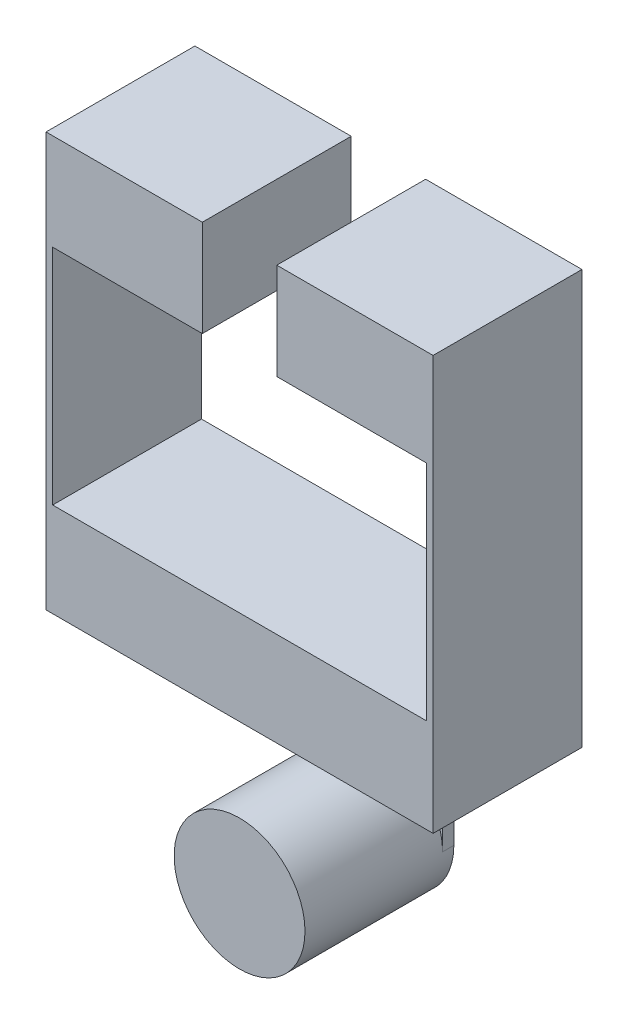
SolidWorks part; units mm, degrees
other "Markup1"
sketch "Sketch7" plane through (31.7043, 97.4003, 0) normal (0.5774, 0.5773, 0.5774) x (0.7071, 0, -0.7071)
material "ASTM A36 Steel"
ref_plane "Front Plane" through (0, 0, 0) normal (0, 0, 1) x (1, 0, 0)
ref_plane "Top Plane" through (0, 0, 0) normal (0, 1, 0) x (1, 0, 0)
ref_plane "Right Plane" through (0, 0, 0) normal (1, 0, 0) x (0, 0, -1)
sketch "Sketch1" plane through (0, 0, 0) normal (0, 0, 1) x (1, 0, 0)
  circle A0 centre (0, 0) radius 11.1628
  dimension "D1" = 22.3256
extrude "Boss-Extrude1" add sketch "Sketch1" against normal blind 25.4
sketch "Sketch2" plane through (0, 0, -25.4) normal (0, 0, -1) x (-1, 0, 0)
  line L0 (-11.1628, 0) -> (-11.1628, 25.4)
  line L1 (-11.1628, 25.4) -> (11.1628, 25.4)
  line L2 (11.1628, 25.4) -> (11.1628, 0)
  circle A0 centre (0, 0) radius 11.1628 construction
  arc A1 (11.1628, 0) -> (-11.1628, 0) centre (0, 0) ccw
  dimension "D1" = 22.3256
  dimension "D2" = 25.4
extrude "Boss-Extrude2" add sketch "Sketch2" against normal blind 1.9264
ref_plane "Plane1" through (0, 25.4, 0) normal (0, 1, 0) x (1, 0, 0)
sketch "Sketch4" plane through (0, 25.4, 0) normal (0, 1, 0) x (1, 0, 0)
  line L0 (0, 0) -> (0, 55.2267) construction
  line L1 (-33.02, 0) -> (33.02, 0)
  line L2 (-33.02, 0) -> (-33.02, 25.4)
  line L3 (-33.02, 25.4) -> (33.02, 25.4)
  line L4 (33.02, 0) -> (33.02, 25.4)
  point P6 (0, 0)
  dimension "D1" = 25.4
  dimension "D2" = 66.04
extrude "Boss-Extrude3" add sketch "Sketch4" along normal blind 16.0644
sketch "Sketch5" plane through (0, 41.4644, 0) normal (0, 1, 0) x (1, 0, 0)
  line L0 (-33.02, 0) -> (33.02, 0) construction
  line L1 (-33.02, 25.4) -> (-31.8904, 25.4)
  line L2 (-33.02, 25.4) -> (-33.02, 0)
  line L3 (-33.02, 0) -> (-31.8904, 0)
  line L4 (-31.8904, 25.4) -> (-31.8904, 0)
  line L6 (33.02, 25.4) -> (31.8904, 25.4)
  line L7 (33.02, 25.4) -> (33.02, 0)
  line L8 (33.02, 0) -> (31.8904, 0)
  line L9 (31.8904, 25.4) -> (31.8904, 0)
  dimension "D1" = 1.1296
  dimension "D2" = 1.1296
extrude "Boss-Extrude4" add sketch "Sketch5" along normal blind 38.1
sketch "Sketch6" plane through (0, 79.5644, 0) normal (0, 1, 0) x (1, 0, 0)
  line L0 (31.8904, 25.4) -> (-31.8904, 25.4) construction
  line L1 (33.02, 0) -> (6.35, 0)
  line L2 (33.02, 0) -> (33.02, 25.4)
  line L3 (33.02, 25.4) -> (6.35, 25.4)
  line L4 (6.35, 0) -> (6.35, 25.4)
  line L5 (0, 0) -> (0, 25.4) construction
  line L6 (-6.35, 0) -> (-6.35, 25.4)
  line L7 (-33.02, 25.4) -> (-6.35, 25.4)
  line L8 (-33.02, 0) -> (-33.02, 25.4)
  line L9 (-33.02, 0) -> (-6.35, 0)
  dimension "D1" = 26.67
extrude "Boss-Extrude5" add sketch "Sketch6" along normal blind 16.4611
equation "\"F\"= 600"
equation "\"E\"= 29000000"
equation "\"Sy\"= 36000"
equation "\"Tallow\"= 9000"
equation "\"La\"= 1in"
equation "\"SF\"= 4"
equation "\"Z\"=  ( \"SF\" *  ( 2 * \"F\" )  * \"La\" )  /  ( 2 * \"Sy\" ) "
equation "\"Ra\"= ( ( \"Z\" / pi ) * 4 ) ^ ( 1 / 3 )"
equation "\"Bw\"= .879in"
equation "\"Ba\"= ( \"SF\" * \"F\" ) / ( \"Sy\" )"
equation "\"Tb\"= \"Ba\" / \"Bw\""
equation "\"Cw\"=2.6"
equation "\"Ct\"= 1"
equation "\"Ca\"= ( \"SF\" * ( 2 * \"F\" ) ) / \"Sy\""
equation "\"Ch\"= ( \"Z\" * 6 ) ^ ( 1 / 2 )"
equation "\"Da\"= ( \"F\" * \"SF\" ) / ( \"Sy\" )"
equation "\"Dh\"= 1.499"
equation "\"Dw\"= \"Da\" / \"Dh\""
equation "\"Ea\"= ( \"F\" * \"SF\" ) / ( \"Sy\" )"
equation "\"Ew\"=1.05"
equation "\"Ad\"= \"Ra\" * 2"
equation "\"D1@Sketch1\"=\"Ad\""
equation "\"D1@Boss-Extrude1\"=\"La\""
equation "\"D1@Boss-Extrude2\"=\"Tb\""
equation "\"D1@Sketch2\"=\"Ad\""
equation "\"D2@Sketch4\"=\"Cw\""
equation "\"D1@Boss-Extrude3\"=\"Ch\""
equation "\"D1@Sketch5\"=\"Dw\""
equation "\"D2@Sketch5\"=\"Dw\""
equation "\"D1@Sketch6\"=\"Ew\""
equation "\"D1@Boss-Extrude5\"=\"Eh\""
equation "\"Ehtop\"= ( 6 * \"F\" * \"Ew\" * \"SF\" )"
equation "\"Ehbottom\"= ( 1 * \"Sy\" )"
equation "\"Eh\"= ( \"Ehtop\" / \"Ehbottom\" ) ^ ( 1 / 2 )"
